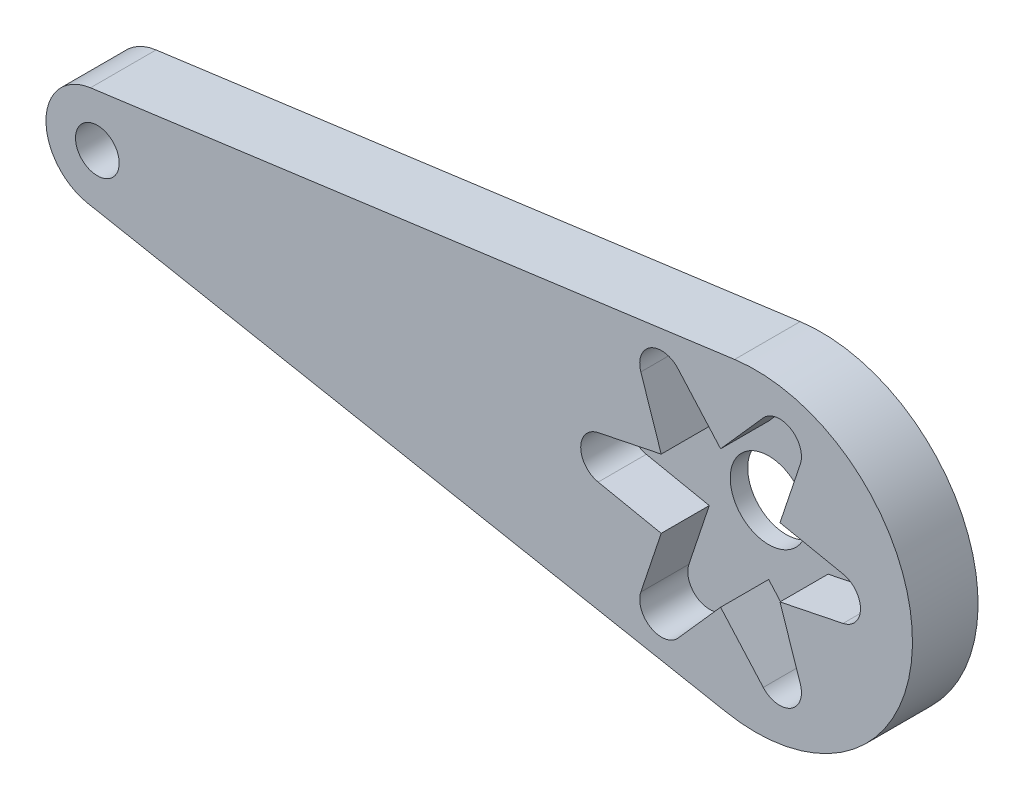
SolidWorks part; units mm, degrees
material "ABS"
ref_plane "Front Plane" through (0, 0, 0) normal (0, 0, 1) x (1, 0, 0)
ref_plane "Top Plane" through (0, 0, 0) normal (0, 1, 0) x (1, 0, 0)
ref_plane "Right Plane" through (0, 0, 0) normal (1, 0, 0) x (0, 0, -1)
sketch "Sketch1" plane through (0, 0, 0) normal (0, 0, 1) x (1, 0, 0)
  line L0 (0, -30.6103) -> (0, -40.6103)
  line L1 (0, -40.6103) -> (99.1041, -59.4601)
  line L2 (99.1041, -59.4601) -> (99.1041, -17.2548)
  line L3 (99.1041, -17.2548) -> (0, -30.6103)
  dimension "D1" = 100
  dimension "D2" = 10
extrude "Boss-Extrude4" add sketch "Sketch1" along normal blind 7.5
fillet "Fillet2" radius 17.9449 4 edges at (99.1041, -38.3574, 7.5) (99.1041, -38.3574, 0) (99.1041, -17.2548, 3.75) (99.1041, -59.4601, 3.75)
fillet "Fillet3" radius 5.8754 4 edges at (0, -35.6103, 0) (0, -40.6103, 3.75) (0, -30.6103, 3.75) (0, -35.6103, 7.5)
sketch "Sketch6" plane through (0, 0, 7.5) normal (0, 0, 1) x (1, 0, 0)
  line L0 (77.1578, -29.6502) -> (82.037, -24.1455)
  line L1 (86.2794, -26.5949) -> (83.9518, -33.5726)
  line L2 (83.9518, -33.5726) -> (91.1585, -35.0458)
  line L3 (91.1585, -39.9445) -> (83.9518, -41.4176)
  line L4 (83.9518, -41.4176) -> (86.2794, -48.3954)
  line L5 (82.037, -50.8447) -> (77.1578, -45.3401)
  line L6 (77.1578, -45.3401) -> (72.2787, -50.8447)
  line L7 (68.0363, -48.3954) -> (70.3639, -41.4176)
  line L8 (70.3639, -41.4176) -> (63.1572, -39.9445)
  line L9 (63.1572, -35.0458) -> (70.3639, -33.5726)
  line L10 (63.1572, -35.0458) -> (70.3639, -33.5726) construction
  line L11 (70.3639, -33.5726) -> (68.0363, -26.5949) construction
  line L12 (70.3639, -33.5726) -> (68.0363, -26.5949)
  line L13 (72.2787, -24.1455) -> (77.1578, -29.6502)
  arc A0 (82.037, -24.1455) -> (86.2794, -26.5949) centre (83.9078, -25.8038) cw
  arc A1 (91.1585, -35.0458) -> (91.1585, -39.9445) centre (90.6578, -37.4951) cw
  arc A2 (86.2794, -48.3954) -> (82.037, -50.8447) centre (83.9078, -49.1865) cw
  arc A3 (72.2787, -50.8447) -> (68.0363, -48.3954) centre (70.4078, -49.1865) cw
  arc A4 (63.1572, -39.9445) -> (63.1572, -35.0458) centre (63.6578, -37.4951) cw
  arc A5 (68.0363, -26.5949) -> (72.2787, -24.1455) centre (70.4078, -25.8038) cw
  circle A6 centre (77.1578, -37.4951) radius 4.4
  circle A7 centre (73.6578, -31.4329) radius 0.75
  circle A8 centre (80.6578, -31.4329) radius 0.75
  circle A9 centre (84.1578, -37.4951) radius 0.75
  circle A10 centre (80.6578, -43.5573) radius 0.75
  circle A11 centre (73.6578, -43.5573) radius 0.75
  circle A12 centre (70.1578, -37.4951) radius 0.75
sketch "Sketch7" plane through (0, 0, 7.5) normal (0, 0, 1) x (1, 0, 0)
  line L0 (70.3639, -33.5726) -> (68.0363, -26.5949)
  line L1 (70.3639, -33.5726) -> (63.1572, -35.0458)
  line L2 (70.3639, -41.4176) -> (63.1572, -39.9445)
  line L3 (70.3639, -41.4176) -> (68.0363, -48.3954)
  line L4 (72.2787, -50.8447) -> (77.1578, -45.3401)
  line L5 (77.1578, -45.3401) -> (82.037, -50.8447)
  line L6 (86.2794, -48.3954) -> (83.9518, -41.4176)
  line L7 (83.9518, -41.4176) -> (91.1585, -39.9445)
  line L8 (91.1585, -35.0458) -> (83.9518, -33.5726)
  line L9 (83.9518, -33.5726) -> (86.2794, -26.5949)
  line L10 (82.037, -24.1455) -> (77.1578, -29.6502)
  line L11 (77.1578, -29.6502) -> (82.037, -24.1455) construction
  line L12 (77.1578, -29.6502) -> (72.2787, -24.1455)
  arc A0 (68.0363, -26.5949) -> (72.2787, -24.1455) centre (70.4078, -25.8038) cw
  arc A1 (82.037, -24.1455) -> (86.2794, -26.5949) centre (83.9078, -25.8038) cw
  arc A2 (91.1585, -35.0458) -> (91.1585, -39.9445) centre (90.6578, -37.4951) cw
  arc A3 (82.037, -50.8447) -> (86.2794, -48.3954) centre (83.9078, -49.1865) ccw
  arc A4 (68.0363, -48.3954) -> (72.2787, -50.8447) centre (70.4078, -49.1865) ccw
  arc A5 (63.1572, -35.0458) -> (63.1572, -39.9445) centre (63.6578, -37.4951) ccw
extrude "Cut-Extrude6" cut sketch "Sketch7" against normal blind 5.5
sketch "Sketch9" plane through (0, 0, 7.5) normal (0, 0, 1) x (1, 0, 0)
  circle A0 centre (77.1578, -37.4951) radius 4.4
extrude "Cut-Extrude8" cut sketch "Sketch9" against normal blind 29
sketch "Sketch10" plane through (0, 0, 7.5) normal (0, 0, 1) x (1, 0, 0)
  circle A0 centre (5.8754, -35.7471) radius 2.5
extrude "Cut-Extrude9" cut sketch "Sketch10" against normal blind 29
